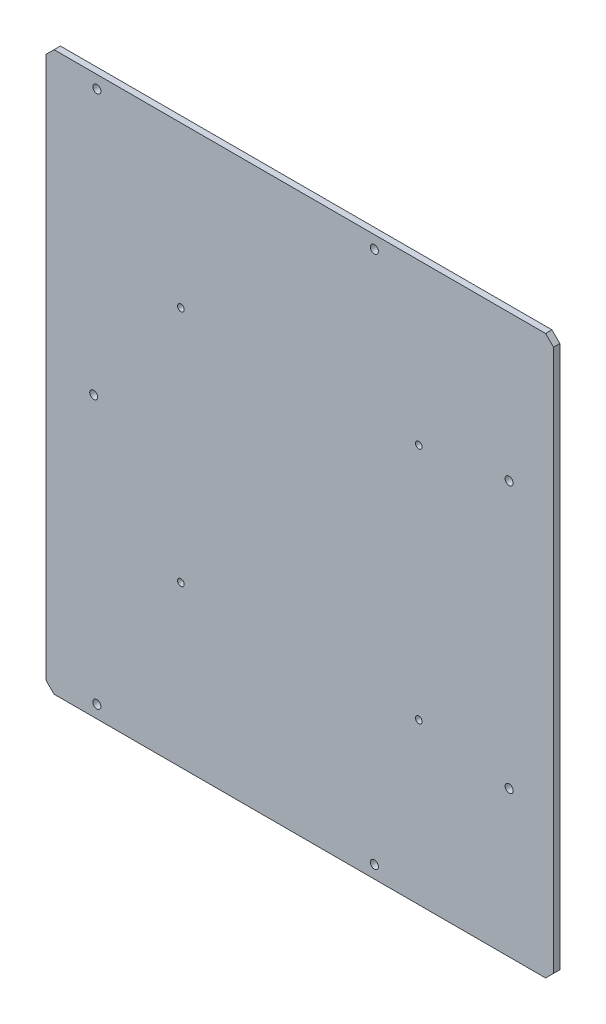
SolidWorks part; units mm, degrees
material "ABS"
ref_plane "Front Plane" through (0, 0, 0) normal (0, 0, 1) x (1, 0, 0)
ref_plane "Top Plane" through (0, 0, 0) normal (0, 1, 0) x (1, 0, 0)
ref_plane "Right Plane" through (0, 0, 0) normal (1, 0, 0) x (0, 0, -1)
sketch "Sketch1" plane through (0, 0, 0) normal (0, 0, 1) x (1, 0, 0)
  line L0 (-155, 176) -> (-160, 171)
  line L1 (155, -176) -> (-155, -176)
  line L2 (160, -171) -> (160, 171)
  line L3 (155, 176) -> (-155, 176)
  line L4 (-160, -171) -> (-160, 171)
  line L5 (160, -176) -> (-160, 176) construction
  line L6 (160, 176) -> (-160, -176) construction
  line L7 (-155, -176) -> (-160, -171)
  line L8 (160, -171) -> (155, -176)
  line L9 (160, 171) -> (155, 176)
  point P0 (0, 0)
  dimension "D1" = 320
  dimension "D2" = 352
extrude "Base" add sketch "Sketch1" along normal blind 4
sketch "Sketch3" plane through (0, 0, 0) normal (0, 0, -1) x (-1, 0, 0)
  line L0 (0, 0) -> (154.2273, 0) construction
  line L2 (160, 171) -> (160, -171) construction
  circle A0 centre (130, 0) radius 2.5
  dimension "D1" = 5
  dimension "D2" = 30
extrude "FittingHole" cut sketch "Sketch3" against normal through all
sketch "Sketch4" plane through (0, 0, 0) normal (0, 0, 1) x (1, 0, 0)
  line L0 (-40.5, -18.9167) -> (-40.5, 0) construction
  line L1 (-40.5, 0) -> (-17.5548, 0) construction
  line L3 (132, -168) -> (-213, -168) construction
  line L5 (132, -168) -> (132, 168) construction
  line L8 (132, 168) -> (-213, 168) construction
  line L9 (-213, -168) -> (-213, 168) construction
  line L10 (132, -168) -> (-213, 168) construction
  line L11 (132, 168) -> (-213, -168) construction
  circle A5 centre (-128, 168) radius 2.55
  circle A8 centre (47, 168) radius 2.55
  circle A9 centre (132, 84) radius 2.55
  circle A10 centre (132, -84) radius 2.55
  circle A11 centre (47, -168) radius 2.55
  circle A12 centre (-128, -168) radius 2.55
  point P16 (-40.5, 0)
  dimension "D5" = 345
  dimension "D2" = 175
  dimension "D7" = 5.1
  dimension "D1" = 168
  dimension "D3" = 40.5
  dimension "D6" = 336
extrude "Cut-Extrude2" cut sketch "Sketch4" along normal through all contours A5 | A8 | A9 | A10 | A11 | A12
sketch "Sketch5" plane through (0, 0, 4) normal (0, 0, 1) x (1, 0, 0)
  line L0 (16.3845, 0) -> (0, 0) construction
  line L1 (0, 0) -> (0, -25.153) construction
  circle A0 centre (-75, -75) radius 2.1
  circle A1 centre (75, -75) radius 2.1
  circle A2 centre (75, 75) radius 2.1
  circle A3 centre (-75, 75) radius 2.1
  dimension "D1" = 4.2
  dimension "D2" = 75
  dimension "D3" = 75
extrude "Cut-Extrude3" cut sketch "Sketch5" against normal through all
